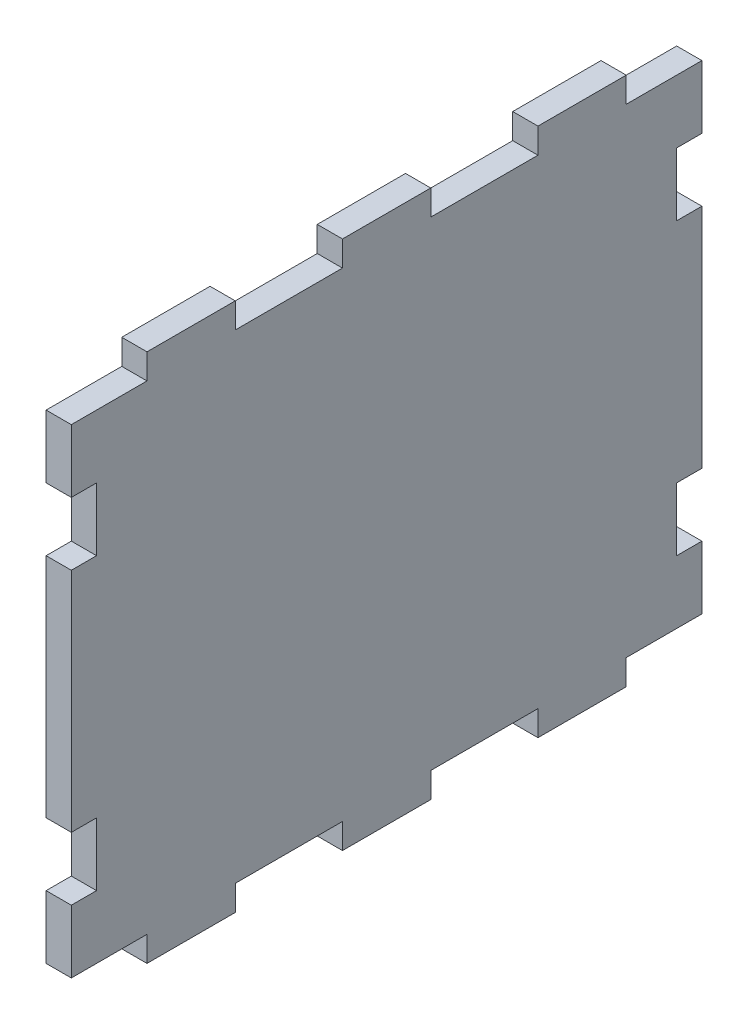
SolidWorks part; units mm, degrees
ref_plane "Front Plane" through (0, 0, 0) normal (0, 0, 1) x (1, 0, 0)
ref_plane "Top Plane" through (0, 0, 0) normal (0, 1, 0) x (1, 0, 0)
ref_plane "Right Plane" through (0, 0, 0) normal (1, 0, 0) x (0, 0, -1)
sketch "Sketch1" plane through (0, 0, 0) normal (1, 0, 0) x (0, 0, -1)
  line L1 (-25, 19) -> (25, 19)
  line L2 (-25, 19) -> (-25, -19)
  line L3 (-25, -19) -> (25, -19)
  line L4 (25, 19) -> (25, -19)
  line L5 (-25, 19) -> (25, -19) construction
  line L6 (-25, -19) -> (25, 19) construction
  line L7 (-19, -19) -> (-12, -19)
  line L8 (-19, -19) -> (-19, -21)
  line L9 (-19, -21) -> (-12, -21)
  line L10 (-12, -19) -> (-12, -21)
  line L11 (-3.5, -19) -> (3.5, -19)
  line L12 (-3.5, -19) -> (-3.5, -21)
  line L13 (-3.5, -21) -> (3.5, -21)
  line L14 (3.5, -19) -> (3.5, -21)
  line L15 (12, -19) -> (19, -19)
  line L16 (12, -19) -> (12, -21)
  line L17 (12, -21) -> (19, -21)
  line L18 (19, -19) -> (19, -21)
  line L19 (-19, 19) -> (-12, 19)
  line L20 (-19, 19) -> (-19, 21)
  line L21 (-19, 21) -> (-12, 21)
  line L22 (-12, 19) -> (-12, 21)
  line L23 (-3.5, 19) -> (3.5, 19)
  line L24 (-3.5, 19) -> (-3.5, 21)
  line L25 (-3.5, 21) -> (3.5, 21)
  line L26 (3.5, 19) -> (3.5, 21)
  line L27 (12, 19) -> (19, 19)
  line L28 (12, 19) -> (12, 21)
  line L29 (12, 21) -> (19, 21)
  line L30 (19, 19) -> (19, 21)
  line L31 (-25, -9) -> (-23, -9)
  line L32 (-25, -9) -> (-25, -14)
  line L33 (-25, -14) -> (-23, -14)
  line L34 (-23, -9) -> (-23, -14)
  line L35 (23, -9) -> (25, -9)
  line L36 (23, -9) -> (23, -14)
  line L37 (23, -14) -> (25, -14)
  line L38 (25, -9) -> (25, -14)
  line L39 (-25, 14) -> (-23, 14)
  line L40 (-25, 14) -> (-25, 9)
  line L41 (-25, 9) -> (-23, 9)
  line L42 (-23, 14) -> (-23, 9)
  line L43 (23, 14) -> (25, 14)
  line L44 (23, 14) -> (23, 9)
  line L45 (23, 9) -> (25, 9)
  line L46 (25, 14) -> (25, 9)
  point P0 (0, 0)
  dimension "D1" = 50
  dimension "D2" = 7
  dimension "D3" = 7
  dimension "D4" = 7
  dimension "D5" = 7
  dimension "D6" = 7
  dimension "D7" = 7
  dimension "D8" = 6
  dimension "D9" = 8.5
  dimension "D10" = 8.5
  dimension "D11" = 6
  dimension "D12" = 6
  dimension "D13" = 8.5
  dimension "D14" = 8.5
  dimension "D15" = 6
  dimension "D16" = 38
  dimension "D17" = 2
  dimension "D18" = 2
  dimension "D19" = 2
  dimension "D20" = 2
  dimension "D21" = 2
  dimension "D22" = 2
  dimension "D23" = 5
  dimension "D24" = 5
  dimension "D25" = 5
  dimension "D26" = 5
  dimension "D27" = 5
  dimension "D28" = 5
  dimension "D29" = 5
  dimension "D30" = 5
  dimension "D31" = 0
  dimension "D32" = 0
  dimension "D33" = 46
  dimension "D34" = 0
  dimension "D35" = 0
  dimension "D37" = 0
  dimension "D38" = 0
extrude "Boss-Extrude1" add sketch "Sketch1" along normal blind 2 contours L4 L1 L2 L3 | L1 L26 L25 L24 | L1 L30 L29 L28 | L18 L3 L16 L17 | L14 L3 L12 L13 | L10 L3 L8 L9 | L22 L21 L20 L19
